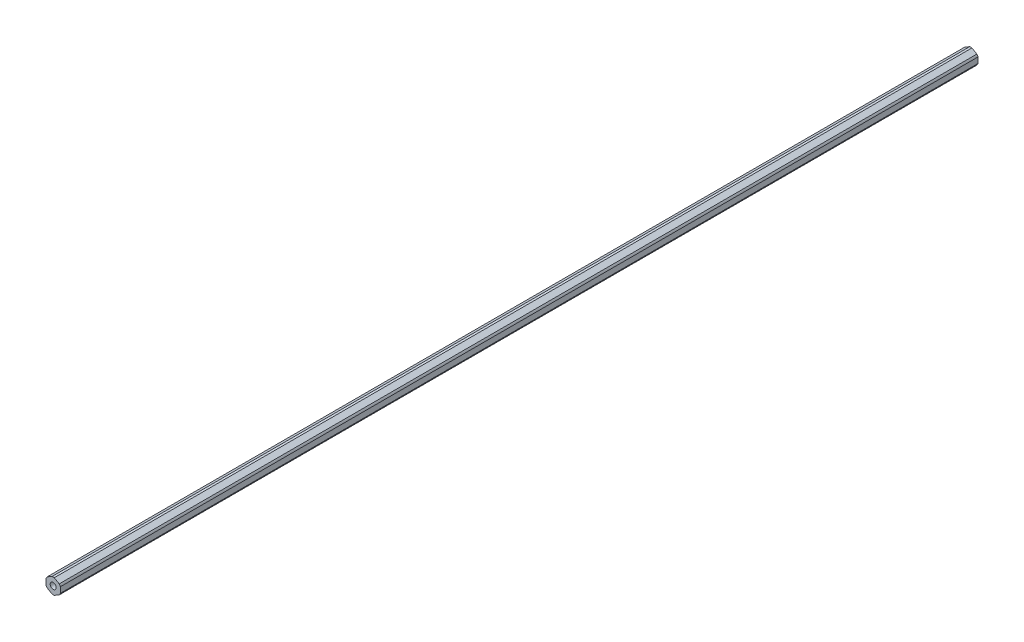
SolidWorks part; units mm, degrees
material "7075-T6 (SN)"
ref_plane "Front Plane" through (0, 0, 0) normal (0, 0, 1) x (1, 0, 0)
ref_plane "Top Plane" through (0, 0, 0) normal (0, 1, 0) x (1, 0, 0)
ref_plane "Right Plane" through (0, 0, 0) normal (1, 0, 0) x (0, 0, -1)
sketch "Sketch2" plane through (0, 0, 0) normal (0, 0, 1) x (1, 0, 0)
  line L1 (0, 5.4993) -> (-4.7625, 2.7496)
  line L2 (-4.7625, 2.7496) -> (-4.7625, -2.7496)
  line L3 (-4.7625, -2.7496) -> (0, -5.4993)
  line L4 (0, -5.4993) -> (4.7625, -2.7496)
  line L5 (4.7625, -2.7496) -> (4.7625, 2.7496)
  line L6 (4.7625, 2.7496) -> (0, 5.4993)
  circle A0 centre (0, 0) radius 4.7625 construction
  circle A2 centre (0, 0) radius 2.0193
  circle A3 centre (0, 0) radius 5.125
  dimension "D1" = 9.525
  dimension "D2" = 10.25
  dimension "D3" = 4.0386
extrude "Boss-Extrude1" add sketch "Sketch2" along normal mid plane 609.6 contours L5 A3 L6 L1 L2 L3 L4 A2
hole_wizard "#10-32 Tapped Hole2" positions "3DSketch1" profile "Sketch6" tap size "#10-32" standard "ANSI Inch"
sketch3d "3DSketch1"
  circle A0 centre (0, 0, 304.8) radius 2.0193 construction
  circle A1 centre (0, 0, -304.8) radius 2.0193 construction
  point P0 (0, 0, -304.8)
  point P2 (0, 0, 304.8)
  point P7 (0, 0, 306.8193)
  point P10 (0, 0, -302.7807)
sketch "Sketch6" plane through (0, 0, -304.8) normal (1, 0, 0) x (0, 1, 0)
  line L0 (0, 0) -> (0, 17.5608)
  line L1 (0, 17.5608) -> (2.0193, 16.3474)
  line L2 (2.0193, 16.3474) -> (2.0193, 0)
  line L5 (2.0193, 0) -> (0, 0)
  line L10 (0, 17.5608) -> (-2.0193, 16.3474) construction
  line L11 (0, -6.35) -> (0, 107.95) construction
  dimension "Tap Drill Dia." = 4.0386
  dimension "Tap Drill Depth" = 16.3474
  dimension "Drill Angle" = 118
cosmetic thread "Hole Thread2"
cosmetic thread "Hole Thread3"
equation "\"D2@Sketch2\"=10.25mm"
